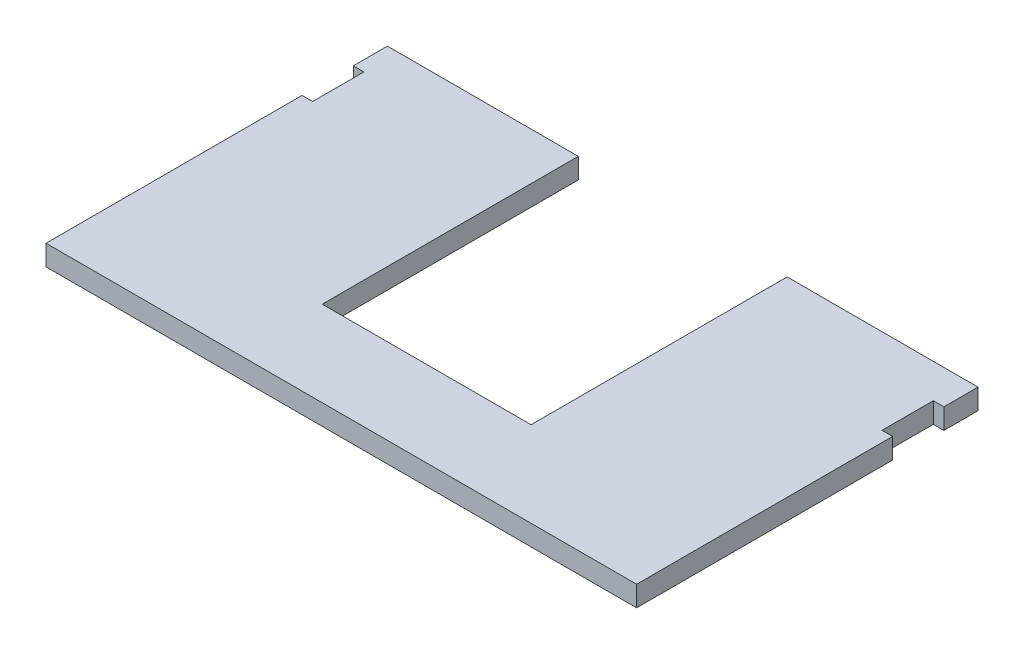
SolidWorks part; units mm, degrees
ref_plane "Front Plane" through (0, 0, 0) normal (0, 0, 1) x (1, 0, 0)
ref_plane "Top Plane" through (0, 0, 0) normal (0, 1, 0) x (1, 0, 0)
ref_plane "Right Plane" through (0, 0, 0) normal (1, 0, 0) x (0, 0, -1)
sketch "Sketch1" plane through (0, 0, 0) normal (0, 1, 0) x (1, 0, 0)
  line L0 (86.5, -920) -> (86.5, 49080) construction
  line L1 (0, 0) -> (173, 0)
  line L2 (0, 0) -> (0, 100)
  line L3 (0, 100) -> (173, 100)
  line L4 (173, 0) -> (173, 100)
  line L5 (55.915, 100) -> (117.085, 100)
  line L6 (55.915, 100) -> (55.915, 25)
  line L7 (55.915, 25) -> (117.085, 25)
  line L8 (117.085, 100) -> (117.085, 25)
  line L9 (0, 90) -> (3.1, 90)
  line L10 (0, 90) -> (0, 75)
  line L11 (0, 75) -> (3.1, 75)
  line L12 (3.1, 90) -> (3.1, 75)
  line L13 (173, 75) -> (169.9, 75)
  line L14 (169.9, 90) -> (169.9, 75)
  line L15 (173, 90) -> (169.9, 90)
  line L16 (173, 90) -> (173, 75)
  point P9 (86.5, 25)
  point P10 (86.5, 0)
  point P18 (86.5, 100)
  dimension "D1" = 173
  dimension "D2" = 100
  dimension "D3" = 61.17
  dimension "D4" = 75
  dimension "D5" = 3.1
  dimension "D6" = 15
  dimension "D7" = 10
extrude "Boss-Extrude1" add sketch "Sketch1" along normal blind 6 contours L1 L0 L7 L6 L3 L2 L9 L12 L11 L10 | L0 L1 L4 L3 L8 L7 L15 L16 L13 L14
